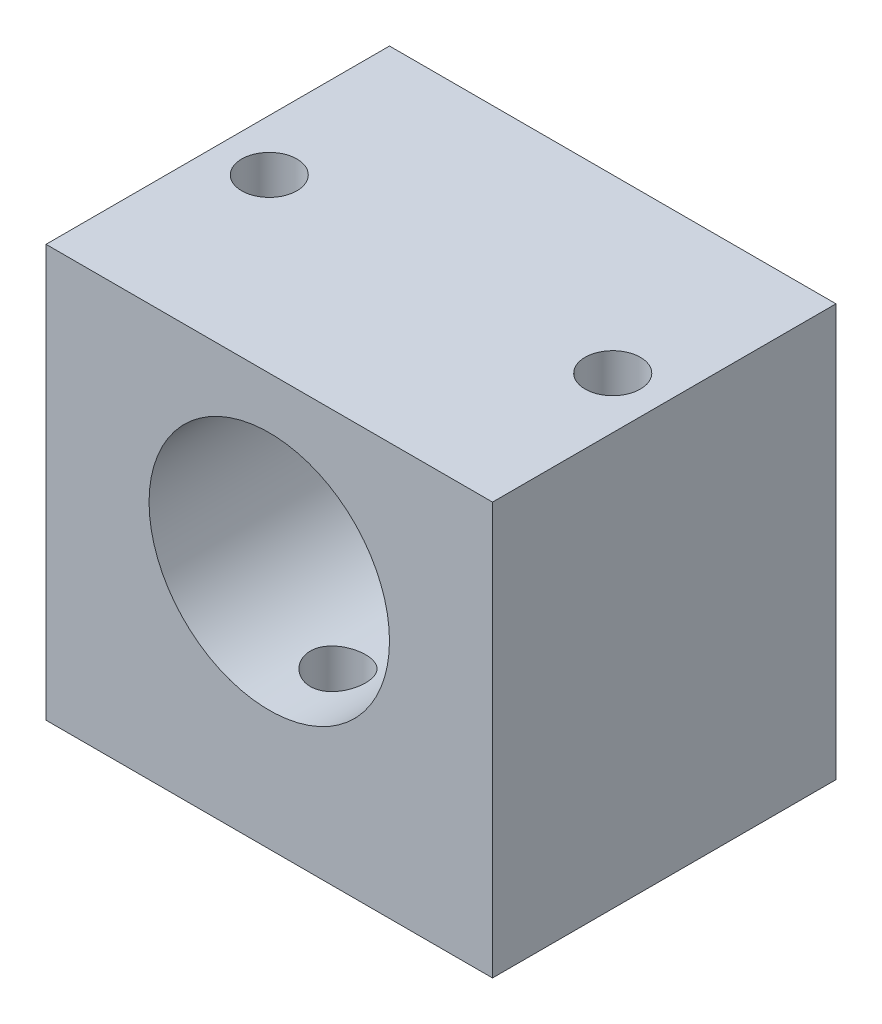
SolidWorks part; units mm, degrees
ref_plane "Front Plane" through (0, 0, 0) normal (0, 0, 1) x (1, 0, 0)
ref_plane "Top Plane" through (0, 0, 0) normal (0, 1, 0) x (1, 0, 0)
ref_plane "Right Plane" through (0, 0, 0) normal (1, 0, 0) x (0, 0, -1)
sketch "Sketch1" plane through (0, 0, 0) normal (1, 0, 0) x (0, 0, -1)
  line L1 (-15.875, 19.05) -> (15.875, 19.05)
  line L2 (-15.875, 19.05) -> (-15.875, -19.05)
  line L3 (-15.875, -19.05) -> (15.875, -19.05)
  line L4 (15.875, 19.05) -> (15.875, -19.05)
  line L5 (-15.875, 19.05) -> (15.875, -19.05) construction
  line L6 (-15.875, -19.05) -> (15.875, 19.05) construction
  point P0 (0, 0)
  dimension "D1" = 31.75
  dimension "D2" = 38.1
extrude "Boss-Extrude1" add sketch "Sketch1" along normal mid plane 41.275
hole_wizard "Hole1" positions "Sketch4" profile "Sketch3" legacy end condition up to next
sketch "Sketch4" plane through (0, 0, 15.875) normal (0, 0, 1) x (1, 0, 0)
  line L0 (20.6375, 19.05) -> (-20.6375, 19.05) construction
  line L1 (0, 3.175) -> (0, 0) construction
  point P0 (0, 3.175)
  dimension "D1" = 15.875
sketch "Sketch3" plane through (0, 3.175, 15.875) normal (1, 0, 0) x (0, -1, 0)
  line L0 (0, 0) -> (0, 31.75)
  line L1 (0, 31.75) -> (11.1125, 31.75)
  line L2 (11.1125, 31.75) -> (11.1125, 0)
  line L3 (11.1125, 0) -> (0, 0)
  line L4 (0, 110) -> (0, -10) construction
  dimension "Diameter" = 22.225
  dimension "Depth" = 31.75
hole_wizard "Tapped Hole for #10-32 Helicoil1" positions "Sketch6" profile "Sketch7" tap size "#10-32" standard "Helicoil® Inch" end condition up to next
sketch "Sketch6" plane through (0, 19.05, 0) normal (0, 1, 0) x (1, 0, 0)
  line L0 (-20.6375, 0) -> (20.6375, 0) construction
  line L1 (-20.6375, 15.875) -> (-20.6375, -15.875) construction
  line L2 (20.6375, 15.875) -> (20.6375, -15.875) construction
  point P8 (-15.875, 0)
  point P10 (15.875, 0)
  dimension "D1" = 4.7625
  dimension "D2" = 4.7625
sketch "Sketch7" plane through (-15.875, 19.05, 0) normal (1, 0, 0) x (0, 0, 1)
  line L0 (0, 0) -> (0, 38.1)
  line L1 (0, 38.1) -> (2.5527, 38.1)
  line L2 (2.5527, 38.1) -> (2.5527, 0)
  line L5 (2.5527, 0) -> (0, 0)
  line L11 (0, -6.35) -> (0, 107.95) construction
  dimension "Thru Tap Drill Dia." = 5.1054
  dimension "Thru Tap Drill Depth" = 38.1
cosmetic thread "Hole Thread1"
cosmetic thread "Hole Thread2"
hole_wizard "Tapped Hole for #10-32 Helicoil2" positions "Sketch9" profile "Sketch8" tap size "#10-32" standard "Helicoil® Inch"
sketch "Sketch9" plane through (0, -19.05, 0) normal (0, -1, 0) x (-1, 0, 0)
  line L0 (0, -15.875) -> (0, 15.875) construction
  line L1 (-20.6375, -15.875) -> (20.6375, -15.875) construction
  line L2 (-20.6375, 15.875) -> (20.6375, 15.875) construction
  point P0 (0, 9.525)
  point P2 (0, -9.525)
  dimension "D1" = 6.35
  dimension "D2" = 6.35
cosmetic thread "Hole Thread3"
cosmetic thread "Hole Thread4"
sketch "Sketch8" plane through (0, -19.05, -9.525) normal (1, 0, 0) x (0, 0, -1)
  line L0 (0, 0) -> (0, 11.1125)
  line L1 (0, 11.1125) -> (2.5527, 11.1125)
  line L2 (2.5527, 11.1125) -> (2.5527, 0)
  line L5 (2.5527, 0) -> (0, 0)
  line L11 (0, -6.35) -> (0, 107.95) construction
  dimension "Thru Tap Drill Dia." = 5.1054
  dimension "Thru Tap Drill Depth" = 11.1125
